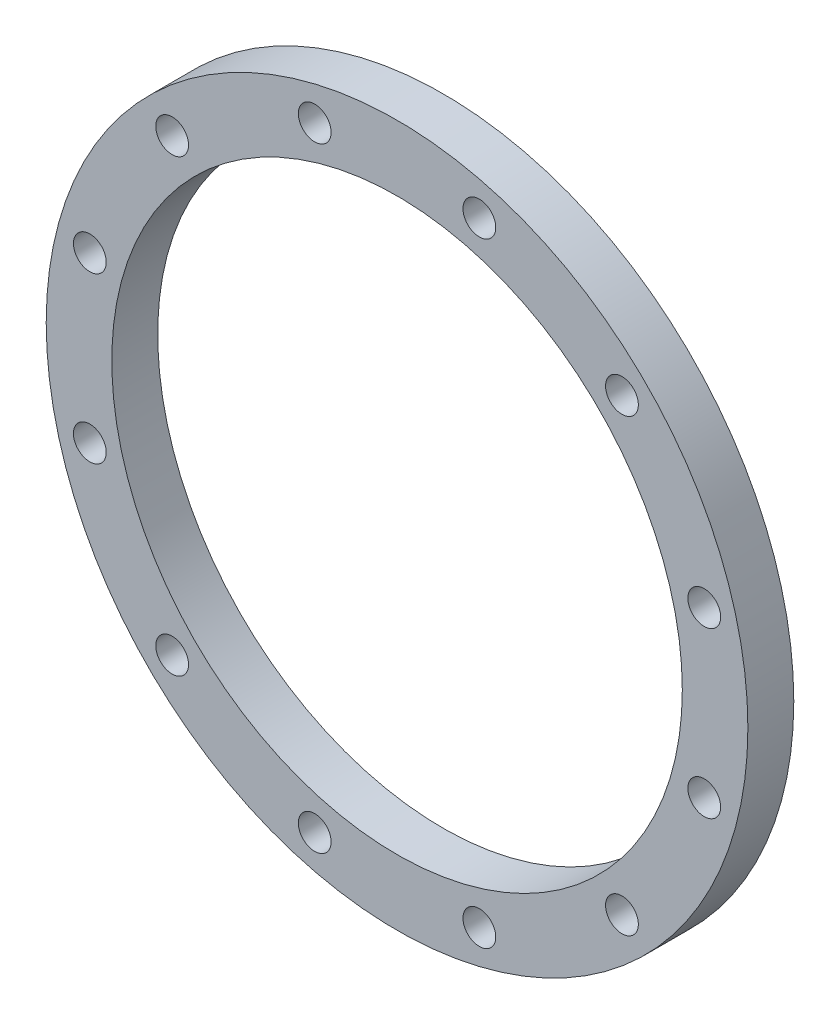
SolidWorks part; units mm, degrees
material "Stainless Steel 2205"
ref_plane "Front Plane" through (0, 0, 0) normal (0, 0, 1) x (1, 0, 0)
ref_plane "Top Plane" through (0, 0, 0) normal (0, 1, 0) x (1, 0, 0)
ref_plane "Right Plane" through (0, 0, 0) normal (1, 0, 0) x (0, 0, -1)
sketch "Sketch1" plane through (0, 0, 0) normal (0, 0, 1) x (1, 0, 0)
  circle A0 centre (0, 0) radius 435
  circle A1 centre (0, 0) radius 535
  dimension "D1" = 870
  dimension "D2" = 100
extrude "Boss-Extrude1" add sketch "Sketch1" along normal blind 70
sketch "Sketch3" plane through (0, 0, 70) normal (0, 0, 1) x (1, 0, 0)
  line L0 (0, 0) -> (0, 485) construction
  line L1 (125.5272, 468.474) -> (0, 0) construction
  line L2 (0, 0) -> (125.5272, 468.474) construction
  line L3 (0, 0) -> (342.9468, 342.9468) construction
  circle A0 centre (0, 0) radius 485 construction
  circle A1 centre (0, 0) radius 535 construction
  circle A2 centre (125.5272, 468.474) radius 25
  circle A3 centre (342.9468, 342.9468) radius 25
  circle A4 centre (468.474, 125.5272) radius 25
  circle A5 centre (468.474, -125.5272) radius 25
  circle A6 centre (342.9468, -342.9468) radius 25
  circle A7 centre (125.5272, -468.474) radius 25
  circle A8 centre (-125.5272, -468.474) radius 25
  circle A9 centre (-342.9468, -342.9468) radius 25
  circle A10 centre (-468.474, -125.5272) radius 25
  circle A11 centre (-468.474, 125.5272) radius 25
  circle A12 centre (-342.9468, 342.9468) radius 25
  circle A13 centre (-125.5272, 468.474) radius 25
  dimension "D1" = 50
  dimension "D2" = 50
  dimension "D3" = 15
  dimension "D5" = 30
  dimension "D4" = 12
extrude "Cut-Extrude2" cut sketch "Sketch3" against normal through all both and the other way through all
equation "\"hatchHoleDiameter\"= 600mm"
equation "\"hullThickness\"= 120mm"
equation "\"gasketHullInterconnectWidth\"= 100mm"
equation "\"collarThickness\"= 15"
equation "\"hatchTunnelLength\"=200"
equation "\"oRingDiameter\"=2"
equation "\"boltPatternRadiusInterconnect\"=500"
equation "\"interconnectBoltDiameter\"=30"
equation "\"hatchShaftDiameter\"=20"
equation "\"hatchMinima\"=50"
equation "\"hullDiameter\"=2000"
equation "\"hatchMaxima\"=180"
equation "\"bushingFlatHatch\"=15"
equation "\"hingePivotDiameter\"=20"
equation "\"handleWidth\"=250"
equation "\"handleHeight\"=160"
equation "\"handleThickness\"=25"
equation "\"FrameLength\"= 4300"
equation "\"FrameMidLength\"= 3000"
equation "\"TubeOD\"= 100"
equation "\"FrameBackFlat\"= 800"
equation "\"TubeWall\"=15"
equation "\"TopMemberAngle\"=120"
equation "\"FrameHight\"= 2500"
equation "\"D1@Sketch1\"=\"hatchHoleDiameter\" + 2 * \"collarThickness\"+\"hullThickness\"*2"
